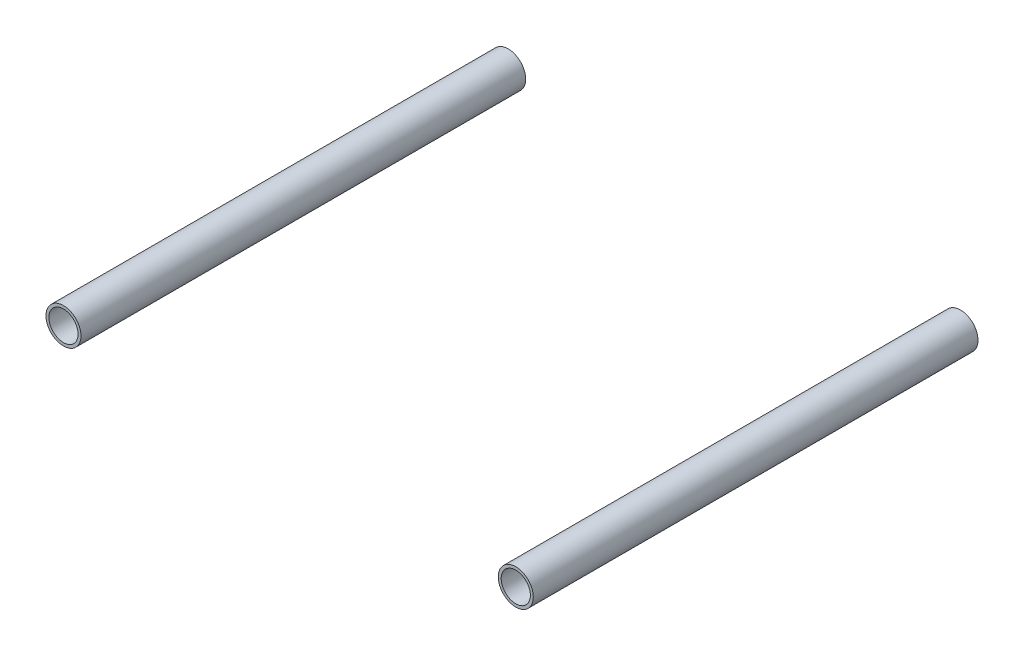
SolidWorks part; units mm, degrees
ref_plane "Front" through (0, 0, 0) normal (0, 0, 1) x (1, 0, 0)
ref_plane "Top" through (0, 0, 0) normal (0, 1, 0) x (1, 0, 0)
ref_plane "Right" through (0, 0, 0) normal (1, 0, 0) x (0, 0, -1)
sketch "Sketch1" plane through (0, 0, 0) normal (0, 0, 1) x (1, 0, 0)
  line L0 (0, 47.6293) -> (0, -61.2732) construction
  line L1 (77.5, 0) -> (-77.5, 0) construction
  circle A1 centre (-77.5, 0) radius 6
  circle A3 centre (-77.5, 0) radius 5
  circle A4 centre (77.5, 0) radius 5
  circle A6 centre (77.5, 0) radius 6
  point P13 (0, 0)
  dimension "D1" = 12
  dimension "D3" = 77.5
  dimension "D5" = 1
extrude "Boss-Extrude1" add sketch "Sketch1" against normal mid plane 152.4
